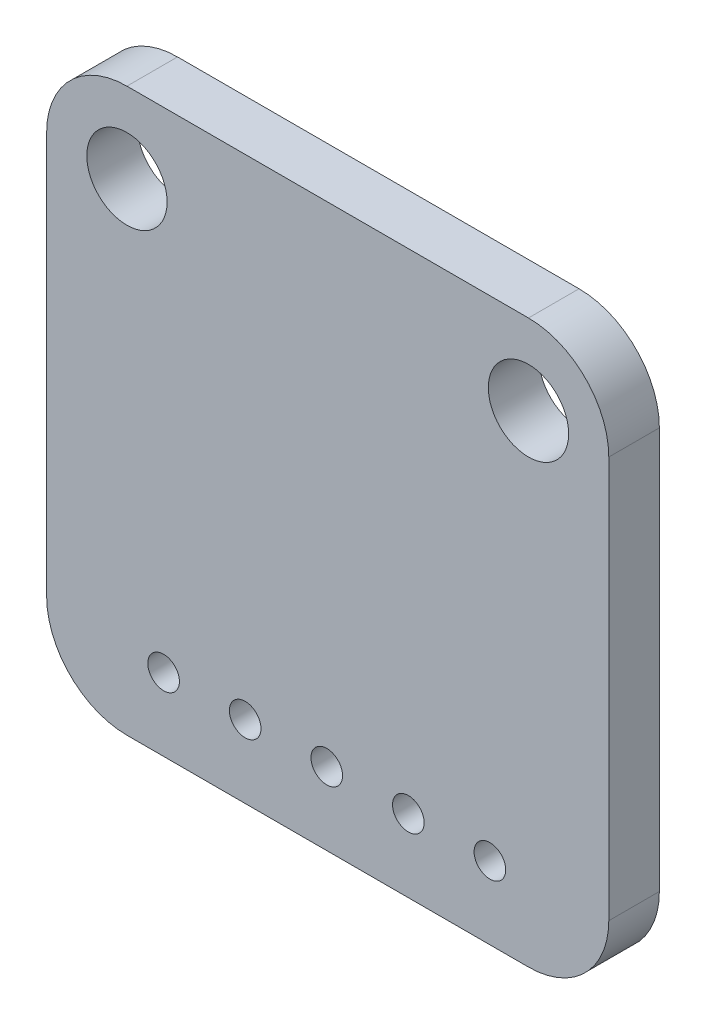
SolidWorks part; units mm, degrees
ref_plane "Front Plane" through (0, 0, 0) normal (0, 0, 1) x (1, 0, 0)
ref_plane "Top Plane" through (0, 0, 0) normal (0, 1, 0) x (1, 0, 0)
ref_plane "Right Plane" through (0, 0, 0) normal (1, 0, 0) x (0, 0, -1)
sketch "Sketch2" plane through (0, 0, 0) normal (0, 0, 1) x (1, 0, 0)
  line L1 (-6.35, -8.89) -> (6.35, -8.89)
  line L2 (-8.89, -6.35) -> (-8.89, 6.35)
  line L3 (-6.35, 8.89) -> (6.35, 8.89)
  line L4 (8.89, -6.35) -> (8.89, 6.35)
  line L5 (-8.89, -8.89) -> (8.89, 8.89) construction
  line L6 (-8.89, 8.89) -> (8.89, -8.89) construction
  arc A1 (6.35, 8.89) -> (8.89, 6.35) centre (6.35, 6.35) cw
  arc A2 (6.35, -8.89) -> (8.89, -6.35) centre (6.35, -6.35) ccw
  arc A3 (-6.35, -8.89) -> (-8.89, -6.35) centre (-6.35, -6.35) cw
  arc A4 (-8.89, 6.35) -> (-6.35, 8.89) centre (-6.35, 6.35) cw
  circle A5 centre (-6.35, 6.35) radius 1.27
  circle A6 centre (6.35, 6.35) radius 1.27
  circle A7 centre (6.35, -6.35) radius 1.27 [skipped]
  circle A8 centre (-6.35, -6.35) radius 1.27 [skipped]
  point P0 (0, 0)
  point P28 (0, 0)
  dimension "D3" = 2.54
  dimension "D4" = 2.54
  dimension "D1" = 17.78
  dimension "D2" = 17.78
extrude "Boss-Extrude1" add sketch "Sketch2" along normal blind 1.6
sketch "Sketch3" plane through (0, 0, 1.6) normal (0, 0, 1) x (1, 0, 0)
  line L0 (-6.35, -8.89) -> (6.35, -8.89) construction
  line L2 (-8.89, 6.35) -> (-8.89, -6.35) construction
  circle A0 centre (-5.19, -6.59) radius 0.5
  circle A1 centre (-2.61, -6.59) radius 0.5
  circle A2 centre (-0.03, -6.59) radius 0.5
  circle A3 centre (2.55, -6.59) radius 0.5
  circle A4 centre (5.13, -6.59) radius 0.5
  dimension "D1" = 1
  dimension "D2" = 2.3
  dimension "D3" = 3.7
  dimension "D4" = 5
extrude "Cut-Extrude1" cut sketch "Sketch3" against normal through all both and the other way through all
